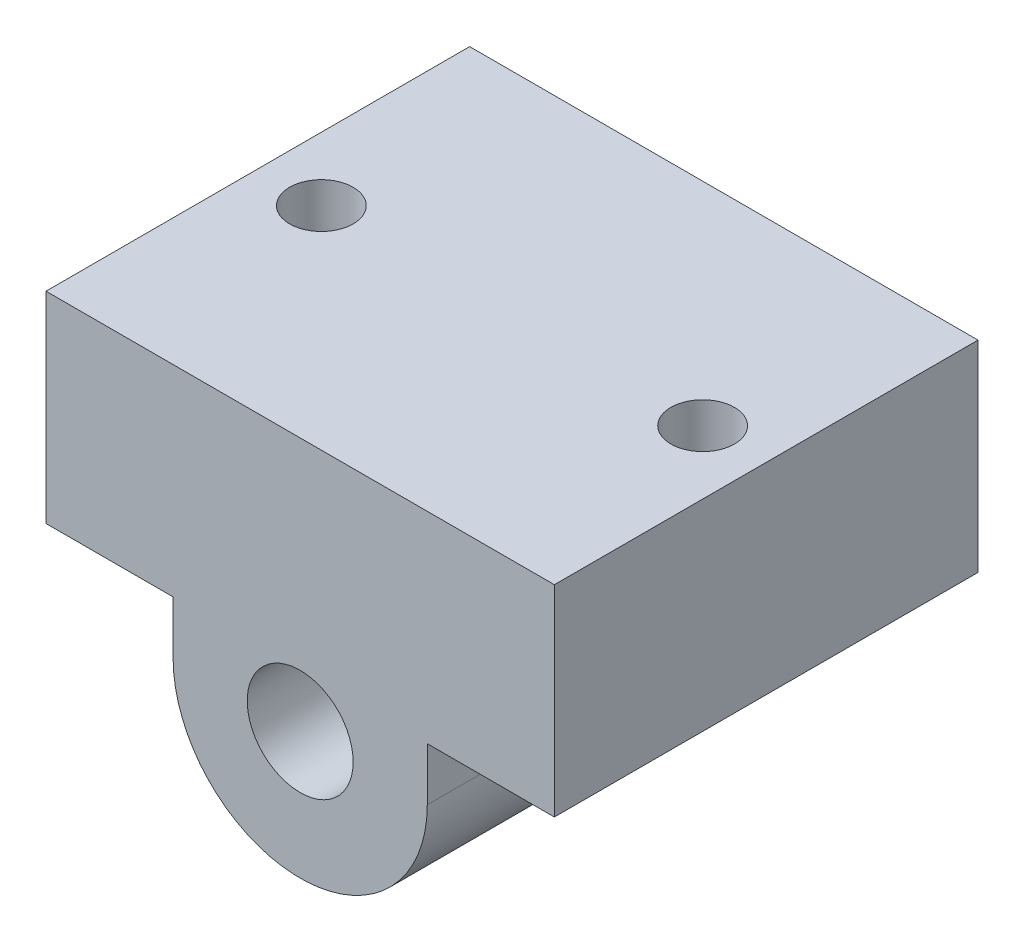
SolidWorks part; units mm, degrees
ref_plane "Plan de face" through (0, 0, 0) normal (0, 0, 1) x (1, 0, 0)
ref_plane "Plan de dessus" through (0, 0, 0) normal (0, 1, 0) x (1, 0, 0)
ref_plane "Plan de droite" through (0, 0, 0) normal (1, 0, 0) x (0, 0, -1)
sketch "Esquisse1" plane through (0, 0, 0) normal (0, 0, 1) x (1, 0, 0)
  line L0 (-6, 0) -> (-6, 12)
  line L1 (-6, 12) -> (6, 12)
  line L2 (6, 12) -> (6, 0)
  line L3 (0, 2.5) -> (12, 2.5) construction
  line L4 (12, 2.5) -> (12, 12) construction
  line L5 (12, 12) -> (-12, 12) construction
  line L6 (-12, 12) -> (-12, 2.5) construction
  line L7 (-12, 2.5) -> (0, 2.5) construction
  line L8 (-6, 12) -> (-12, 12)
  line L9 (-12, 12) -> (-12, 2.5)
  line L10 (-12, 2.5) -> (12, 2.5)
  line L11 (12, 2.5) -> (12, 12)
  line L12 (12, 12) -> (-6, 12)
  circle A0 centre (0, 0) radius 2.5
  circle A1 centre (0, 0) radius 6
  circle A2 centre (0, 0) radius 2.9
  dimension "D1" = 5
  dimension "D2" = 12
  dimension "D6" = 5.8
  dimension "D3" = 12
  dimension "D4" = 12
  dimension "D5" = 12
extrude "Boss.-Extru.1" add sketch "Esquisse1" against normal blind 20 contours A1 L10 L2 L1 L0 | L11 L12 L2 L10 | A1 L10 L0 | A1 L10 A0 | A1 L2 L10 | L10 A1 | A2
sketch "Esquisse2" plane through (0, 2.5, 0) normal (0, -1, 0) x (1, 0, 0)
  line L0 (-6, 0) -> (-12, -20) construction
  line L1 (-12, -20) -> (-12, 0) construction
  line L2 (-12, 0) -> (-6, -20) construction
  line L3 (6, 0) -> (12, -20) construction
  line L4 (12, -20) -> (6, -20) construction
  line L5 (6, -20) -> (12, 0) construction
  circle A0 centre (-9, -10) radius 1.5
  circle A1 centre (9, -10) radius 1.5
  dimension "D1" = 3
  dimension "D2" = 3
extrude "Enlèv. mat.-Extru.1" cut sketch "Esquisse2" against normal blind 10
